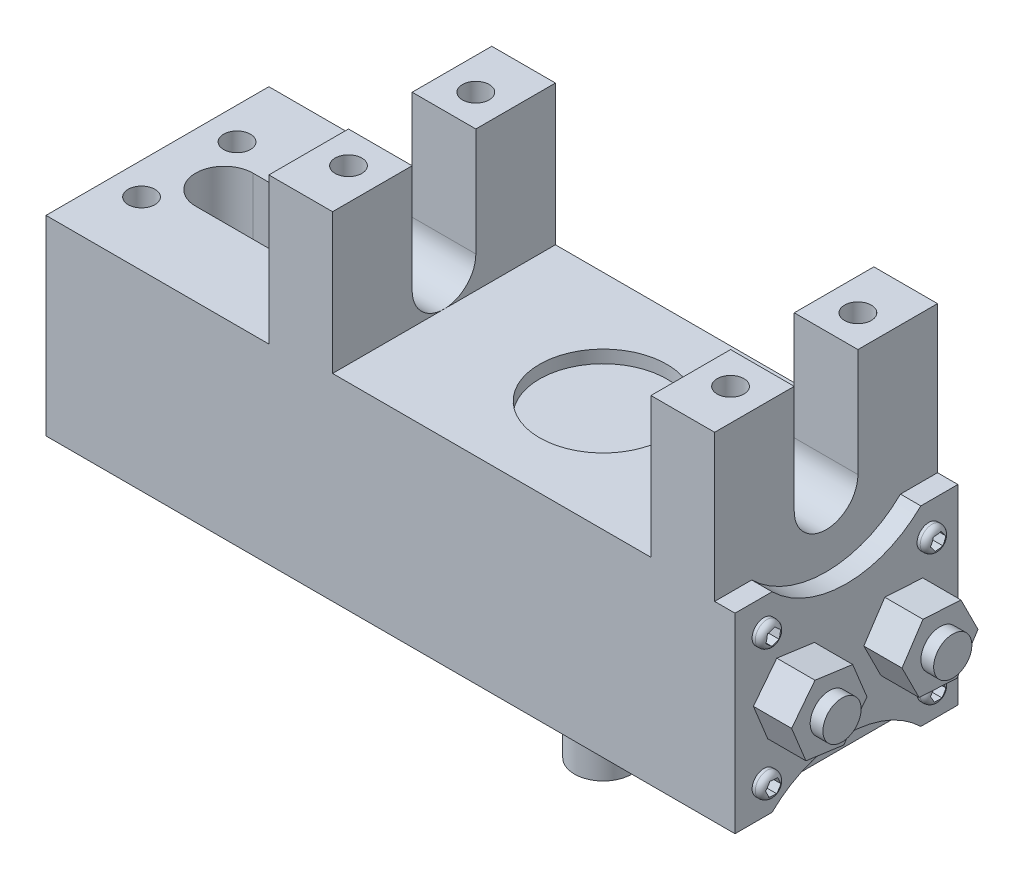
SolidWorks part; units mm, degrees
ref_plane "前视基准面" through (0, 0, 0) normal (0, 0, 1) x (1, 0, 0)
ref_plane "上视基准面" through (0, 0, 0) normal (0, 1, 0) x (1, 0, 0)
ref_plane "右视基准面" through (0, 0, 0) normal (1, 0, 0) x (0, 0, -1)
sketch "草图1" plane through (0, 0, 0) normal (0, 1, 0) x (1, 0, 0)
  line L0 (0, 0) -> (0, 41.8136) construction
  line L1 (-35, 17.5) -> (35, 17.5)
  line L2 (-35, 17.5) -> (-35, -17.5)
  line L3 (-35, -17.5) -> (35, -17.5)
  line L4 (35, 17.5) -> (35, -17.5)
  line L5 (0, 0) -> (78.2893, 0) construction
  dimension "D1" = 70
  dimension "D2" = 35
extrude "凸台-拉伸1" add sketch "草图1" along normal blind 53
sketch "草图2" plane through (0, 0, 17.5) normal (0, 0, 1) x (1, 0, 0)
  line L0 (-35, 53) -> (35, 53) construction
  line L1 (-25, 53) -> (25, 53)
  line L2 (-25, 53) -> (-25, 31)
  line L3 (-25, 31) -> (25, 31)
  line L4 (25, 53) -> (25, 31)
  line L5 (0, 0) -> (0, 64.9299) construction
  dimension "D1" = 50
  dimension "D2" = 22
extrude "切除-拉伸1" cut sketch "草图2" against normal through all
sketch "草图3" plane through (0, 31, 0) normal (0, 1, 0) x (1, 0, 0)
  circle A0 centre (0, 0) radius 10
  dimension "D1" = 20
extrude "切除-拉伸2" cut sketch "草图3" against normal blind 2
sketch "草图4" plane through (0, 0, 0) normal (0, -1, 0) x (1, 0, 0)
  circle A0 centre (0, 0) radius 14
  dimension "D1" = 28
extrude "凸台-拉伸2" add sketch "草图4" along normal blind 2
sketch "草图5" plane through (0, -2, 0) normal (0, -1, 0) x (1, 0, 0)
  circle A0 centre (0, 0) radius 4.5
  dimension "D1" = 9
extrude "凸台-拉伸3" add sketch "草图5" along normal blind 15.5
sketch "草图6" plane through (35, 0, 0) normal (1, 0, 0) x (0, 0, -1)
  line L0 (-5, 53) -> (-5, 36)
  line L1 (-17.5, 53) -> (17.5, 53) construction
  line L2 (5, 36) -> (5, 53)
  line L3 (5, 53) -> (-5, 53)
  line L4 (17.5, 31) -> (-17.5, 31) construction
  arc A0 (-5, 36) -> (5, 36) centre (0, 36) ccw
  dimension "D1" = 10
extrude "切除-拉伸3" cut sketch "草图6" against normal through all
hole_wizard "M5x0.8 螺纹孔1" positions "草图8" profile "草图7" tap size "M5x0.8" standard "JIS"
sketch "草图8" plane through (0, 53, 0) normal (0, 1, 0) x (-1, 0, 0)
  line L0 (0, 0) -> (0, -22.5367) construction
  line L2 (0, 0) -> (-41.7053, 0) construction
  point P0 (-30, -10)
  point P1 (30, -10)
  point P3 (30, 10)
  point P5 (-30, 10)
  dimension "D1" = 20
  dimension "D2" = 60
sketch "草图7" plane through (30, 53, -10) normal (1, 0, 0) x (0, 0, 1)
  line L0 (0, 0) -> (0, 13.6618)
  line L1 (0, 13.6618) -> (2.1, 12.4)
  line L2 (2.1, 12.4) -> (2.1, 0)
  line L5 (2.1, 0) -> (0, 0)
  line L10 (0, 13.6618) -> (-2.1, 12.4) construction
  line L11 (0, -6.35) -> (0, 107.95) construction
  dimension "螺纹孔钻头直径" = 4.2
  dimension "螺纹孔钻头深度" = 12.4
  dimension "导头角度" = 118
cosmetic thread "孔螺蚊线1" parameters "D1"=10, "D2"=5
cosmetic thread "孔螺蚊线2" parameters "D1"=10, "D2"=5
cosmetic thread "孔螺蚊线3" parameters "D1"=10, "D2"=5
cosmetic thread "孔螺蚊线4" parameters "D1"=10, "D2"=5
sketch "草图9" plane through (35, 0, 0) normal (1, 0, 0) x (0, 0, -1)
  line L0 (-17.5, 30) -> (-17.5, 0)
  line L1 (-17.5, 53) -> (-17.5, 0) construction
  line L2 (-17.5, 0) -> (17.5, 0)
  line L3 (17.5, 53) -> (17.5, 0) construction
  line L4 (17.5, 0) -> (17.5, 30)
  line L5 (17.5, 30) -> (-17.5, 30)
  line L6 (-17.5, 0) -> (17.5, 0) construction
  dimension "D1" = 30
extrude "凸台-拉伸4" add sketch "草图9" along normal blind 3.2
sketch "草图10" plane through (38.2, 0, 0) normal (1, 0, 0) x (0, 0, -1)
  line L0 (-17.5, 15) -> (27.7334, 15) construction
  line L1 (-17.5, 30) -> (-17.5, 0) construction
  circle A0 centre (0, 41.9896) radius 16.7389
  circle A1 centre (0, -11.9896) radius 16.7389
extrude "切除-拉伸4" cut sketch "草图10" against normal up to surface (3.2 mm away) up to face at (35, 45.25, -2.1875)
sketch "草图11" plane through (38.2, 0, 0) normal (1, 0, 0) x (0, 0, -1)
  line L0 (0, 25.2507) -> (0, 4.7493) construction
  line L1 (-17.5, 15) -> (17.5, 15) construction
  line L2 (-17.5, 30) -> (-17.5, 0) construction
  line L3 (17.5, 0) -> (17.5, 30) construction
  circle A0 centre (-12.9507, 25.2561) radius 1.8679
  arc A1 (-11.6808, 30) -> (11.6808, 30) centre (0, 41.9896) ccw construction
  arc A2 (11.6808, 0) -> (-11.6808, 0) centre (0, -11.9896) ccw construction
  circle A3 centre (-12.9507, 4.7439) radius 1.8679
  circle A4 centre (12.9507, 4.7439) radius 1.8679
  circle A5 centre (12.9507, 25.2561) radius 1.8679
extrude "凸台-拉伸5" add sketch "草图11" along normal blind 1.5
fillet "圆角1" radius 1 4 edges at (39.7, 4.7439, 14.8186) (39.7, 4.7439, -14.8186) (39.7, 25.2561, -11.0829) (39.7, 25.2561, 11.0829)
sketch "草图12" plane through (39.7, 0, 0) normal (1, 0, 0) x (0, 0, -1)
  line L1 (-12.7108, 26.449) -> (-13.8639, 26.0604)
  line L2 (-13.8639, 26.0604) -> (-14.1038, 24.8675)
  line L3 (-14.1038, 24.8675) -> (-13.1907, 24.0632)
  line L4 (-13.1907, 24.0632) -> (-12.0376, 24.4518)
  line L5 (-12.0376, 24.4518) -> (-11.7976, 25.6447)
  line L6 (-11.7976, 25.6447) -> (-12.7108, 26.449)
  line L7 (13.4168, 26.3801) -> (12.2103, 26.2217)
  line L8 (12.2103, 26.2217) -> (11.7443, 25.0977)
  line L9 (11.7443, 25.0977) -> (12.4847, 24.1321)
  line L10 (12.4847, 24.1321) -> (13.6912, 24.2905)
  line L11 (13.6912, 24.2905) -> (14.1572, 25.4145)
  line L12 (14.1572, 25.4145) -> (13.4168, 26.3801)
  line L13 (13.5702, 5.7913) -> (12.3534, 5.804)
  line L14 (12.3534, 5.804) -> (11.734, 4.7567)
  line L15 (11.734, 4.7567) -> (12.3313, 3.6965)
  line L16 (12.3313, 3.6965) -> (13.5481, 3.6838)
  line L17 (13.5481, 3.6838) -> (14.1675, 4.7311)
  line L18 (14.1675, 4.7311) -> (13.5702, 5.7913)
  line L19 (-12.2615, 5.7467) -> (-13.4746, 5.8422)
  line L20 (-13.4746, 5.8422) -> (-14.1638, 4.8394)
  line L21 (-14.1638, 4.8394) -> (-13.64, 3.7411)
  line L22 (-13.64, 3.7411) -> (-12.4269, 3.6456)
  line L23 (-12.4269, 3.6456) -> (-11.7377, 4.6484)
  line L24 (-11.7377, 4.6484) -> (-12.2615, 5.7467)
  circle A0 centre (-12.9507, 25.2561) radius 1.0538 construction
  circle A1 centre (12.9507, 25.2561) radius 1.0538 construction
  circle A2 centre (12.9507, 4.7439) radius 1.0538 construction
  circle A3 centre (-12.9507, 4.7439) radius 1.0538 construction
extrude "切除-拉伸5" cut sketch "草图12" against normal blind 5
sketch "草图13" plane through (38.2, 0, 0) normal (1, 0, 0) x (0, 0, -1)
  line L0 (0, 25.2507) -> (0, 4.7493) construction
  circle A0 centre (-8.6932, 15.067) radius 3
  arc A1 (-11.6808, 30) -> (11.6808, 30) centre (0, 41.9896) ccw construction
  arc A2 (11.6808, 0) -> (-11.6808, 0) centre (0, -11.9896) ccw construction
  circle A3 centre (8.6932, 15.067) radius 3
  dimension "D1" = 6
extrude "凸台-拉伸6" add sketch "草图13" along normal blind 8
sketch "草图14" plane through (38.2, 0, 0) normal (1, 0, 0) x (0, 0, -1)
  line L1 (-5.0239, 19.7822) -> (-10.9421, 20.6023)
  line L2 (-10.9421, 20.6023) -> (-14.6114, 15.8871)
  line L3 (-14.6114, 15.8871) -> (-12.3625, 10.3517)
  line L4 (-12.3625, 10.3517) -> (-6.4443, 9.5317)
  line L5 (-6.4443, 9.5317) -> (-2.775, 14.2469)
  line L6 (-2.775, 14.2469) -> (-5.0239, 19.7822)
  line L7 (11.9812, 20.0556) -> (6.0169, 20.4088)
  line L8 (6.0169, 20.4088) -> (2.7289, 15.4201)
  line L9 (2.7289, 15.4201) -> (5.4052, 10.0783)
  line L10 (5.4052, 10.0783) -> (11.3695, 9.7252)
  line L11 (11.3695, 9.7252) -> (14.6575, 14.7138)
  line L12 (14.6575, 14.7138) -> (11.9812, 20.0556)
  circle A0 centre (-8.6932, 15.067) radius 5.1743 construction
  circle A1 centre (8.6932, 15.067) radius 5.1743 construction
extrude "凸台-拉伸7" add sketch "草图14" along normal blind 6
sketch "草图15" plane through (-35, 0, 0) normal (-1, 0, 0) x (0, 0, 1)
  line L0 (17.5, 53) -> (17.5, 0) construction
  line L1 (-17.5, 0) -> (17.5, 0)
  line L2 (-17.5, 0) -> (-17.5, 30)
  line L3 (-17.5, 30) -> (17.5, 30)
  line L4 (17.5, 0) -> (17.5, 30)
  dimension "D1" = 30
extrude "凸台-拉伸8" add sketch "草图15" along normal blind 35
sketch "草图16" plane through (0, 30, 0) normal (0, 1, 0) x (1, 0, 0)
  line L0 (-59.5, 0) -> (-45.5, 0) construction
  line L1 (-59.5, 4.5) -> (-45.5, 4.5)
  line L2 (-59.5, -4.5) -> (-45.5, -4.5)
  line L3 (-52.5, 17.5) -> (-52.5, 0) construction
  line L4 (-70, 17.5) -> (-35, 17.5) construction
  arc A0 (-59.5, 4.5) -> (-59.5, -4.5) centre (-59.5, 0) ccw
  arc A1 (-45.5, -4.5) -> (-45.5, 4.5) centre (-45.5, 0) ccw
  point P3 (-52.5, 0)
  dimension "D2" = 4.5
  dimension "D1" = 14
extrude "切除-拉伸6" cut sketch "草图16" against normal blind 35
hole_wizard "M5x0.8 螺纹孔2" positions "草图18" profile "草图17" tap size "M5x0.8" standard "JIS"
sketch "草图18" plane through (0, 30, 0) normal (0, 1, 0) x (-1, 0, 0)
  line L0 (70, 0) -> (55.9335, 0) construction
  line L1 (70, 17.5) -> (70, -17.5) construction
  point P0 (65, -7.5)
  point P1 (65, 7.5)
  dimension "D1" = 15
  dimension "D2" = 5
sketch "草图17" plane through (-65, 30, -7.5) normal (1, 0, 0) x (0, 0, 1)
  line L0 (0, 0) -> (0, 13.6618)
  line L1 (0, 13.6618) -> (2.1, 12.4)
  line L2 (2.1, 12.4) -> (2.1, 0)
  line L5 (2.1, 0) -> (0, 0)
  line L10 (0, 13.6618) -> (-2.1, 12.4) construction
  line L11 (0, -6.35) -> (0, 107.95) construction
  dimension "螺纹孔钻头直径" = 4.2
  dimension "螺纹孔钻头深度" = 12.4
  dimension "导头角度" = 118
cosmetic thread "孔螺蚊线5" parameters "D1"=10, "D2"=5
cosmetic thread "孔螺蚊线6" parameters "D1"=10, "D2"=5
sketch "草图19" plane through (-70, 0, 0) normal (-1, 0, 0) x (0, 0, 1)
  line L0 (0, 30) -> (0, 0) construction
  line L1 (17.5, 30) -> (-17.5, 30) construction
  line L2 (-14, 0) -> (14, 0) construction
  line L3 (-17.5, 15) -> (17.5, 15) construction
  line L4 (-17.5, 30) -> (-17.5, 0) construction
  line L5 (17.5, 0) -> (17.5, 30) construction
  circle A0 centre (-12.2658, 25.045) radius 2.5
  circle A1 centre (-12.2658, 4.955) radius 2.5
  circle A2 centre (12.2658, 4.955) radius 2.5
  circle A3 centre (12.2658, 25.045) radius 2.5
  dimension "D1" = 5
extrude "凸台-拉伸9" add sketch "草图19" along normal blind 1.5
fillet "圆角2" radius 1 4 edges at (-71.5, 4.955, -14.7658) (-71.5, 4.955, 14.7658) (-71.5, 25.045, 9.7658) (-71.5, 25.045, -9.7658)
sketch "草图20" plane through (-71.5, 0, 0) normal (-1, 0, 0) x (0, 0, 1)
  line L1 (-12.2658, 26.1908) -> (-13.2581, 25.6179)
  line L2 (-13.2581, 25.6179) -> (-13.2581, 24.4721)
  line L3 (-13.2581, 24.4721) -> (-12.2658, 23.8991)
  line L4 (-12.2658, 23.8991) -> (-11.2735, 24.4721)
  line L5 (-11.2735, 24.4721) -> (-11.2735, 25.6179)
  line L6 (-11.2735, 25.6179) -> (-12.2658, 26.1908)
  line L7 (13.1663, 25.6179) -> (12.1489, 26.2344)
  line L8 (12.1489, 26.2344) -> (11.1062, 25.6615)
  line L9 (11.1062, 25.6615) -> (11.081, 24.4721)
  line L10 (11.081, 24.4721) -> (12.0985, 23.8555)
  line L11 (12.0985, 23.8555) -> (13.1412, 24.4285)
  line L12 (13.1412, 24.4285) -> (13.1663, 25.6179)
  line L13 (12.6576, 5.9756) -> (11.5779, 5.8046)
  line L14 (11.5779, 5.8046) -> (11.1861, 4.784)
  line L15 (11.1861, 4.784) -> (11.8741, 3.9345)
  line L16 (11.8741, 3.9345) -> (12.9538, 4.1055)
  line L17 (12.9538, 4.1055) -> (13.3456, 5.1261)
  line L18 (13.3456, 5.1261) -> (12.6576, 5.9756)
  line L19 (-11.53, 5.8046) -> (-12.6337, 6.017)
  line L20 (-12.6337, 6.017) -> (-13.3695, 5.1675)
  line L21 (-13.3695, 5.1675) -> (-13.0016, 4.1055)
  line L22 (-13.0016, 4.1055) -> (-11.898, 3.893)
  line L23 (-11.898, 3.893) -> (-11.1622, 4.7426)
  line L24 (-11.1622, 4.7426) -> (-11.53, 5.8046)
  circle A0 centre (-12.2658, 25.045) radius 0.9923 construction
  circle A1 centre (12.1237, 25.045) radius 1.0303 construction
  circle A2 centre (12.2658, 4.955) radius 0.9467 construction
  circle A3 centre (-12.2658, 4.955) radius 0.9733 construction
extrude "切除-拉伸7" cut sketch "草图20" against normal blind 3
